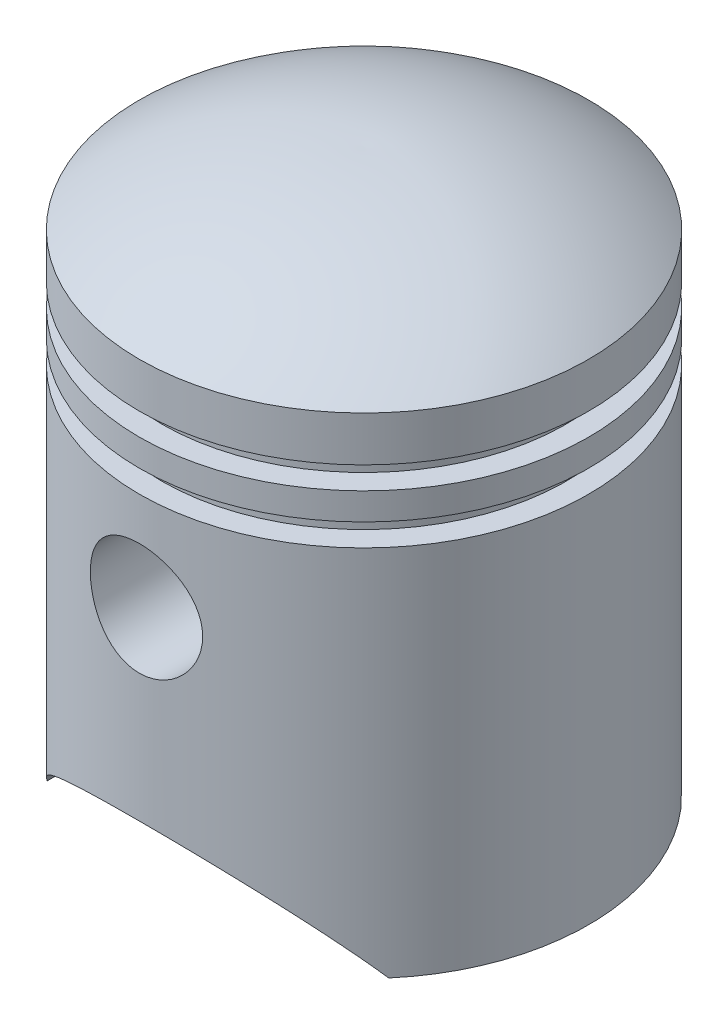
SolidWorks part; units mm, degrees
ref_plane "Front Plane" through (0, 0, 0) normal (0, 0, 1) x (1, 0, 0)
ref_plane "Top Plane" through (0, 0, 0) normal (0, 1, 0) x (1, 0, 0)
ref_plane "Right Plane" through (0, 0, 0) normal (1, 0, 0) x (0, 0, -1)
sketch "Sketch1" plane through (0, 0, 0) normal (0, 0, 1) x (1, 0, 0)
  line L0 (25, 0) -> (25, 41.5)
  line L1 (25, 49.5) -> (22.5, 49.5)
  line L2 (22.5, 49.5) -> (22.5, 47)
  line L3 (22.5, 47) -> (25, 47)
  line L4 (25, 44) -> (22.5, 44)
  line L5 (22.5, 44) -> (22.5, 41.5)
  line L6 (22.5, 41.5) -> (25, 41.5)
  line L7 (25, 49.5) -> (25, 54.5)
  line L8 (25, 44) -> (25, 47)
  line L9 (23, 0) -> (23, 39.5)
  line L10 (20.5, 39.5) -> (23, 39.5)
  line L11 (20.5, 45.5) -> (20.5, 39.5)
  line L12 (20.5, 45.5) -> (20.5, 45.5)
  line L13 (20.5, 45.5) -> (20.5, 45.5)
  line L14 (20.5, 45.5) -> (20.5, 45.5)
  line L15 (20.5, 51.5) -> (20.5, 45.5)
  line L16 (23, 51.5) -> (20.5, 51.5)
  line L17 (23, 51.5) -> (23, 53.4845)
  line L18 (0, 62.5) -> (0, 60.4994)
  line L19 (25, 0) -> (23, 0)
  line L20 (0, 94.01) -> (0, 60.4994) construction
  arc A0 (25, 54.5) -> (0, 62.5) centre (0.9839, 22.5121) ccw
  arc A1 (23, 53.4845) -> (0, 60.4994) centre (0.9839, 22.5121) ccw
  arc A2 (23, 53.4845) -> (0.0492, 60.5006) centre (0.9839, 22.5121) ccw construction
  dimension "D4" = 40
  dimension "D1" = 25
  dimension "D2" = 62.5
  dimension "D3" = 54.5
  dimension "D5" = 5
  dimension "D6" = 2.5
  dimension "D7" = 2.5
  dimension "D8" = 3
  dimension "D9" = 2
  dimension "D10" = 2.5
revolve "Revolve1" add sketch "Sketch1" angle 360 about L20
sketch "Sketch2" plane through (0, 0, 0) normal (0, 0, 1) x (1, 0, 0)
  line L0 (-25, 0) -> (25, 0) construction
  line L1 (-19, 0) -> (19, 0)
  circle A0 centre (0, 30.5) radius 6.25
  arc A1 (-19, 0) -> (19, 0) centre (0, -13.05) cw
  dimension "D1" = 12.5
  dimension "D4" = 10
  dimension "D2" = 32
  dimension "D3" = 38
extrude "Cut-Extrude1" cut sketch "Sketch2" against normal through all both and the other way through all
sketch "Sketch3" plane through (0, 0, 0) normal (0, 0, 1) x (1, 0, 0)
  circle A0 centre (0, 30.5) radius 7.25
  circle A1 centre (0, 30.5) radius 6.25
  dimension "D1" = 14.5
  dimension "D2" = 12.5
extrude "Boss-Extrude2" add sketch "Sketch3" along normal up to surface (11.9257 mm away) from offset 12
mirror "Mirror1" about plane through (0, 0, 0) normal (0, 0, 1) of "Boss-Extrude2"
